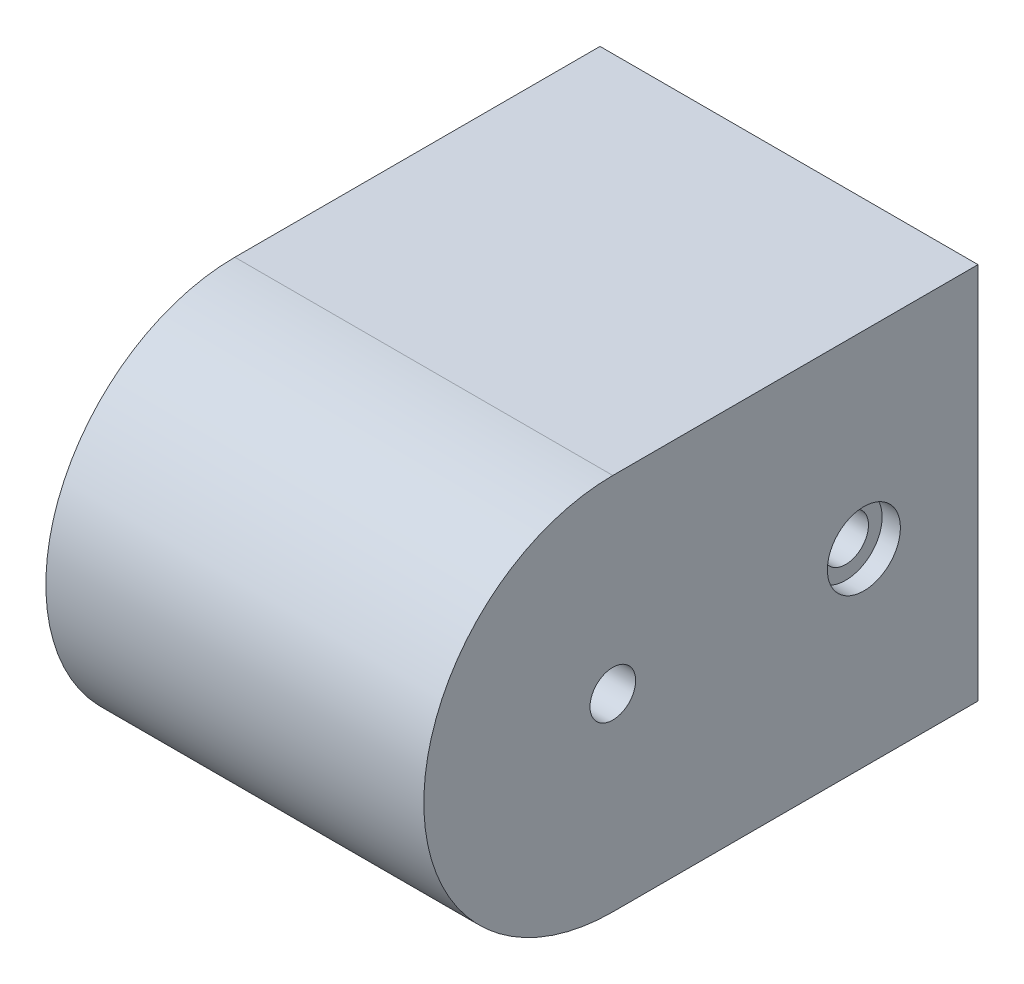
SolidWorks part; units mm, degrees
ref_plane "Front Plane" through (0, 0, 0) normal (0, 0, 1) x (1, 0, 0)
ref_plane "Top Plane" through (0, 0, 0) normal (0, 1, 0) x (1, 0, 0)
ref_plane "Right Plane" through (0, 0, 0) normal (1, 0, 0) x (0, 0, -1)
sketch "Sketch1" plane through (0, 0, 0) normal (0, 0, 1) x (1, 0, 0)
  line L1 (-12.7, 12.7) -> (12.7, 12.7)
  line L2 (-12.7, 12.7) -> (-12.7, -12.7)
  line L3 (-12.7, -12.7) -> (12.7, -12.7)
  line L4 (12.7, 12.7) -> (12.7, -12.7)
  line L5 (-12.7, 12.7) -> (12.7, -12.7) construction
  line L6 (-12.7, -12.7) -> (12.7, 12.7) construction
  line L7 (-20.7, 20.7) -> (20.7, 20.7)
  line L8 (-20.7, 20.7) -> (-20.7, -20.7)
  line L9 (-20.7, -20.7) -> (20.7, -20.7)
  line L10 (20.7, 20.7) -> (20.7, -20.7)
  line L11 (-20.7, 20.7) -> (20.7, -20.7) construction
  line L12 (-20.7, -20.7) -> (20.7, 20.7) construction
  point P0 (0, 0)
  point P6 (0, 0)
  dimension "D1" = 25.4
  dimension "D2" = 8
  dimension "D3" = 8
extrude "Boss-Extrude1" add sketch "Sketch1" along normal blind 30
sketch "Sketch2" plane through (0, 0, 30) normal (0, 0, 1) x (1, 0, 0)
  line L1 (-20.7, 20.7) -> (20.7, 20.7)
  line L2 (-20.7, 20.7) -> (-20.7, -20.7)
  line L3 (-20.7, -20.7) -> (20.7, -20.7)
  line L4 (20.7, 20.7) -> (20.7, -20.7)
  line L5 (-20.7, 20.7) -> (20.7, -20.7) construction
  line L6 (-20.7, -20.7) -> (20.7, 20.7) construction
  point P0 (0, 0)
extrude "Boss-Extrude2" add sketch "Sketch2" along normal blind 10
sketch "Sketch3" plane through (20.7, 0, 0) normal (1, 0, 0) x (0, 0, -1)
  line L0 (-40, -20.7) -> (-40, 20.7)
  line L1 (-40, 20.7) -> (0, 20.7) construction
  arc A0 (-40, -20.7) -> (-40, 20.7) centre (-40, 0) cw
extrude "Boss-Extrude3" add sketch "Sketch3" against normal up to surface (41.4 mm away) up to face at (-20.7, 0, 20)
sketch "Sketch4" plane through (20.7, 0, 0) normal (1, 0, 0) x (0, 0, -1)
  circle A0 centre (-40, 0) radius 2.5
  dimension "D1" = 5
extrude "Cut-Extrude1" cut sketch "Sketch4" against normal up to surface (41.4 mm away) up to face at (-20.7, 0, 25.175)
sketch "Sketch5" plane through (-20.7, 0, 0) normal (-1, 0, 0) x (0, 0, 1)
  line L0 (0, 20.7) -> (0, -20.7) construction
  circle A0 centre (12.5, 0) radius 2.5
  dimension "D1" = 5
  dimension "D2" = 12.5
extrude "Cut-Extrude2" cut sketch "Sketch5" against normal up to surface (41.4 mm away) up to face at (20.7, 0, 37.5)
sketch "Sketch6" plane through (-20.7, 0, 0) normal (-1, 0, 0) x (0, 0, 1)
  circle A0 centre (12.5, 0) radius 4
  dimension "D1" = 8
extrude "Cut-Extrude3" cut sketch "Sketch6" against normal blind 2
sketch "Sketch7" plane through (20.7, 0, 0) normal (1, 0, 0) x (0, 0, -1)
  circle A1 centre (-12.5, 0) radius 4
  dimension "D2" = 8
extrude "Cut-Extrude4" cut sketch "Sketch7" against normal blind 2
